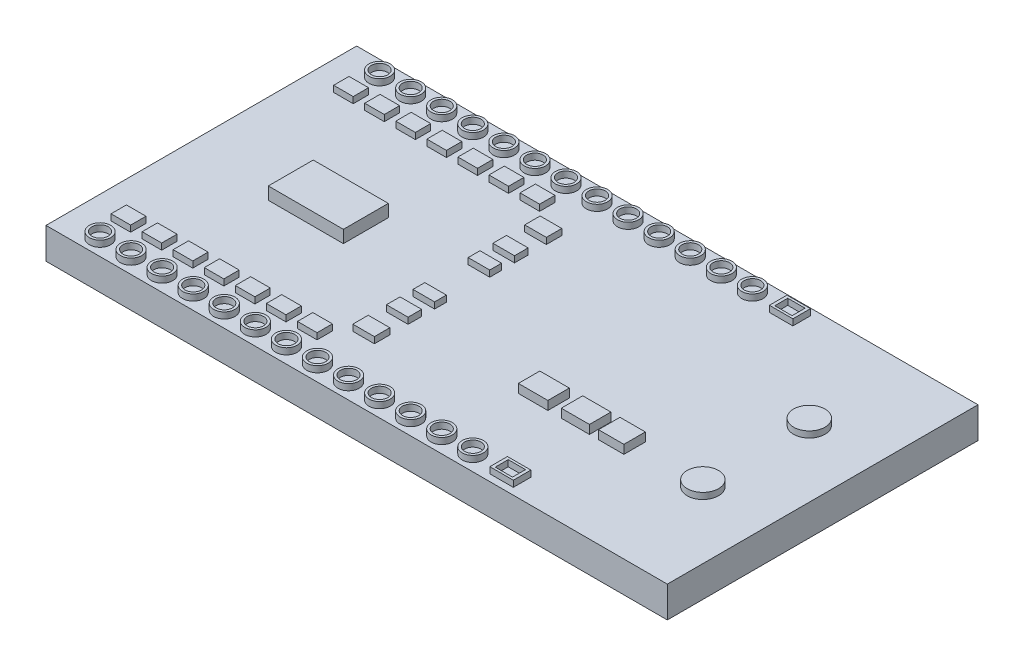
SolidWorks part; units mm, degrees
ref_plane "Front Plane" through (0, 0, 0) normal (0, 0, 1) x (1, 0, 0)
ref_plane "Top Plane" through (0, 0, 0) normal (0, 1, 0) x (1, 0, 0)
ref_plane "Right Plane" through (0, 0, 0) normal (1, 0, 0) x (0, 0, -1)
sketch "Sketch1" plane through (0, 0, 0) normal (0, 1, 0) x (1, 0, 0)
  line L1 (-25, 12.5) -> (25, 12.5)
  line L2 (-25, 12.5) -> (-25, -12.5)
  line L3 (-25, -12.5) -> (25, -12.5)
  line L4 (25, 12.5) -> (25, -12.5)
  line L5 (-25, 12.5) -> (25, -12.5) construction
  line L6 (-25, -12.5) -> (25, 12.5) construction
  point P0 (0, 0)
  dimension "D1" = 25
  dimension "D2" = 50
extrude "Boss-Extrude1" add sketch "Sketch1" along normal blind 2.5
sketch "Sketch2" plane through (0, 2.5, 0) normal (0, 1, 0) x (1, 0, 0)
  line L0 (-35.8947, 0) -> (29.0268, 0) construction
  line L1 (11.8135, -11.7711) -> (11.8135, -10.7261)
  line L2 (10.174, 11.956) -> (12.06, 11.956)
  line L3 (10.174, 11.956) -> (10.174, 10.5412)
  line L4 (10.174, 10.5412) -> (12.06, 10.5412)
  line L5 (12.06, 11.956) -> (12.06, 10.5412)
  line L6 (12.06, -11.956) -> (12.06, -10.5412)
  line L7 (10.174, -11.956) -> (12.06, -11.956)
  line L8 (10.4205, 11.7711) -> (11.8135, 11.7711)
  line L9 (10.4205, 11.7711) -> (10.4205, 10.7261)
  line L10 (10.4205, 10.7261) -> (11.8135, 10.7261)
  line L11 (11.8135, 11.7711) -> (11.8135, 10.7261)
  line L12 (10.4205, -11.7711) -> (11.8135, -11.7711)
  line L13 (10.174, -10.5412) -> (12.06, -10.5412)
  line L14 (10.4205, -10.7261) -> (11.8135, -10.7261)
  line L15 (10.4205, -11.7711) -> (10.4205, -10.7261)
  line L16 (10.174, -11.956) -> (10.174, -10.5412)
  line L17 (-20.1913, 9.5736) -> (-20.1913, 8.3389)
  line L18 (-22.6913, 9.5736) -> (-21.1163, 9.5736)
  line L19 (-22.6913, 9.5736) -> (-22.6913, 8.3389)
  line L20 (-22.6913, 8.3389) -> (-21.1163, 8.3389)
  line L21 (-21.1163, 9.5736) -> (-21.1163, 8.3389)
  line L22 (-22.6913, 9.5736) -> (-21.1163, 8.3389) construction
  line L23 (-22.6913, 8.3389) -> (-21.1163, 9.5736) construction
  line L24 (-20.1913, 9.5736) -> (-18.6163, 9.5736)
  line L25 (-18.6163, 9.5736) -> (-18.6163, 8.3389)
  line L26 (-20.1913, 8.3389) -> (-18.6163, 8.3389)
  line L27 (-17.6913, 9.5736) -> (-17.6913, 8.3389)
  line L28 (-17.6913, 9.5736) -> (-16.1163, 9.5736)
  line L29 (-16.1163, 9.5736) -> (-16.1163, 8.3389)
  line L30 (-17.6913, 8.3389) -> (-16.1163, 8.3389)
  line L31 (-15.1913, 9.5736) -> (-15.1913, 8.3389)
  line L32 (-15.1913, 9.5736) -> (-13.6163, 9.5736)
  line L33 (-13.6163, 9.5736) -> (-13.6163, 8.3389)
  line L34 (-15.1913, 8.3389) -> (-13.6163, 8.3389)
  line L35 (-12.6913, 9.5736) -> (-12.6913, 8.3389)
  line L36 (-12.6913, 9.5736) -> (-11.1163, 9.5736)
  line L37 (-11.1163, 9.5736) -> (-11.1163, 8.3389)
  line L38 (-12.6913, 8.3389) -> (-11.1163, 8.3389)
  line L39 (-10.1913, 9.5736) -> (-10.1913, 8.3389)
  line L40 (-10.1913, 9.5736) -> (-8.6163, 9.5736)
  line L41 (-8.6163, 9.5736) -> (-8.6163, 8.3389)
  line L42 (-10.1913, 8.3389) -> (-8.6163, 8.3389)
  line L43 (-7.6913, 9.5736) -> (-7.6913, 8.3389)
  line L44 (-7.6913, 9.5736) -> (-6.1163, 9.5736)
  line L45 (-6.1163, 9.5736) -> (-6.1163, 8.3389)
  line L46 (-7.6913, 8.3389) -> (-6.1163, 8.3389)
  line L47 (-7.6913, -9.5736) -> (-6.1163, -9.5736)
  line L48 (-6.1163, -9.5736) -> (-6.1163, -8.3389)
  line L49 (-7.6913, -8.3389) -> (-6.1163, -8.3389)
  line L50 (-7.6913, -9.5736) -> (-7.6913, -8.3389)
  line L51 (-10.1913, -9.5736) -> (-8.6163, -9.5736)
  line L52 (-8.6163, -9.5736) -> (-8.6163, -8.3389)
  line L53 (-10.1913, -8.3389) -> (-8.6163, -8.3389)
  line L54 (-10.1913, -9.5736) -> (-10.1913, -8.3389)
  line L55 (-12.6913, -9.5736) -> (-11.1163, -9.5736)
  line L56 (-11.1163, -9.5736) -> (-11.1163, -8.3389)
  line L57 (-12.6913, -8.3389) -> (-11.1163, -8.3389)
  line L58 (-12.6913, -9.5736) -> (-12.6913, -8.3389)
  line L59 (-15.1913, -9.5736) -> (-13.6163, -9.5736)
  line L60 (-13.6163, -9.5736) -> (-13.6163, -8.3389)
  line L61 (-15.1913, -8.3389) -> (-13.6163, -8.3389)
  line L62 (-15.1913, -9.5736) -> (-15.1913, -8.3389)
  line L63 (-17.6913, -9.5736) -> (-16.1163, -9.5736)
  line L64 (-16.1163, -9.5736) -> (-16.1163, -8.3389)
  line L65 (-17.6913, -8.3389) -> (-16.1163, -8.3389)
  line L66 (-17.6913, -9.5736) -> (-17.6913, -8.3389)
  line L67 (-20.1913, -9.5736) -> (-18.6163, -9.5736)
  line L68 (-18.6163, -9.5736) -> (-18.6163, -8.3389)
  line L69 (-20.1913, -8.3389) -> (-18.6163, -8.3389)
  line L70 (-20.1913, -9.5736) -> (-20.1913, -8.3389)
  line L71 (-22.6913, -8.3389) -> (-21.1163, -8.3389)
  line L72 (-21.1163, -9.5736) -> (-21.1163, -8.3389)
  line L73 (-22.6913, -9.5736) -> (-21.1163, -9.5736)
  line L74 (-22.6913, -9.5736) -> (-22.6913, -8.3389)
  line L75 (-5.2732, -6.2958) -> (-3.5344, -6.2958)
  line L76 (-5.2732, 7.5383) -> (-3.5344, 7.5383)
  line L77 (-5.2732, 7.5383) -> (-5.2732, 6.2958)
  line L78 (-5.2732, 6.2958) -> (-3.5344, 6.2958)
  line L79 (-3.5344, 7.5383) -> (-3.5344, 6.2958)
  line L80 (-5.2732, 7.5383) -> (-3.5344, 6.2958) construction
  line L81 (-5.2732, 6.2958) -> (-3.5344, 7.5383) construction
  line L82 (-5.2732, 4.8291) -> (-3.5344, 4.8291)
  line L83 (-5.2732, 4.8291) -> (-5.2732, 3.7363)
  line L84 (-5.2732, 3.7363) -> (-3.5344, 3.7363)
  line L85 (-3.5344, 4.8291) -> (-3.5344, 3.7363)
  line L86 (-5.2732, 4.8291) -> (-3.5344, 3.7363) construction
  line L87 (-5.2732, 3.7363) -> (-3.5344, 4.8291) construction
  line L88 (-5.2732, 2.6954) -> (-3.5344, 2.6954)
  line L89 (-5.2732, 2.6954) -> (-5.2732, 1.7437)
  line L90 (-5.2732, 1.7437) -> (-3.5344, 1.7437)
  line L91 (-3.5344, 2.6954) -> (-3.5344, 1.7437)
  line L92 (-5.2732, 2.6954) -> (-3.5344, 1.7437) construction
  line L93 (-5.2732, 1.7437) -> (-3.5344, 2.6954) construction
  line L94 (-3.5344, -7.5383) -> (-3.5344, -6.2958)
  line L95 (-5.2732, -7.5383) -> (-3.5344, -7.5383)
  line L96 (-5.2732, -7.5383) -> (-5.2732, -6.2958)
  line L97 (-5.2732, -3.7363) -> (-3.5344, -3.7363)
  line L98 (-3.5344, -4.8291) -> (-3.5344, -3.7363)
  line L99 (-5.2732, -4.8291) -> (-3.5344, -4.8291)
  line L100 (-5.2732, -4.8291) -> (-5.2732, -3.7363)
  line L101 (-5.2732, -1.7437) -> (-3.5344, -1.7437)
  line L102 (-3.5344, -2.6954) -> (-3.5344, -1.7437)
  line L103 (-5.2732, -2.6954) -> (-3.5344, -2.6954)
  line L104 (-5.2732, -2.6954) -> (-5.2732, -1.7437)
  line L105 (-5.2732, -1.7437) -> (-3.5344, -2.6954) construction
  line L106 (-5.2732, -2.6954) -> (-3.5344, -1.7437) construction
  circle A0 centre (-21.9038, 11.2486) radius 0.6585
  circle A1 centre (-21.9038, 11.2486) radius 0.858
  circle A2 centre (-19.4038, 11.2486) radius 0.6585
  circle A3 centre (-19.4038, 11.2486) radius 0.858
  circle A4 centre (-16.9038, 11.2486) radius 0.6585
  circle A5 centre (-16.9038, 11.2486) radius 0.858
  circle A6 centre (-14.4038, 11.2486) radius 0.6585
  circle A7 centre (-14.4038, 11.2486) radius 0.858
  circle A8 centre (-11.9038, 11.2486) radius 0.6585
  circle A9 centre (-11.9038, 11.2486) radius 0.858
  circle A10 centre (-9.4038, 11.2486) radius 0.6585
  circle A11 centre (-9.4038, 11.2486) radius 0.858
  circle A12 centre (-6.9038, 11.2486) radius 0.6585
  circle A13 centre (-6.9038, 11.2486) radius 0.858
  circle A14 centre (-4.4038, 11.2486) radius 0.6585
  circle A15 centre (-4.4038, 11.2486) radius 0.858
  circle A16 centre (-1.9038, 11.2486) radius 0.6585
  circle A17 centre (-1.9038, 11.2486) radius 0.858
  circle A18 centre (0.5962, 11.2486) radius 0.6585
  circle A19 centre (0.5962, 11.2486) radius 0.858
  circle A20 centre (3.0962, 11.2486) radius 0.6585
  circle A21 centre (3.0962, 11.2486) radius 0.858
  circle A22 centre (5.5962, 11.2486) radius 0.6585
  circle A23 centre (5.5962, 11.2486) radius 0.858
  circle A24 centre (8.0962, 11.2486) radius 0.6585
  circle A25 centre (8.0962, 11.2486) radius 0.858
  circle A26 centre (-9.4038, -11.2486) radius 0.858
  circle A27 centre (-11.9038, -11.2486) radius 0.858
  circle A28 centre (-11.9038, -11.2486) radius 0.6585
  circle A29 centre (-14.4038, -11.2486) radius 0.858
  circle A30 centre (-4.4038, -11.2486) radius 0.6585
  circle A31 centre (-6.9038, -11.2486) radius 0.6585
  circle A32 centre (-9.4038, -11.2486) radius 0.6585
  circle A33 centre (-14.4038, -11.2486) radius 0.6585
  circle A34 centre (-16.9038, -11.2486) radius 0.858
  circle A35 centre (-16.9038, -11.2486) radius 0.6585
  circle A36 centre (-19.4038, -11.2486) radius 0.858
  circle A37 centre (-19.4038, -11.2486) radius 0.6585
  circle A38 centre (-21.9038, -11.2486) radius 0.6585
  circle A39 centre (-21.9038, -11.2486) radius 0.858
  circle A40 centre (5.5962, -11.2486) radius 0.6585
  circle A41 centre (5.5962, -11.2486) radius 0.858
  circle A42 centre (8.0962, -11.2486) radius 0.858
  circle A43 centre (8.0962, -11.2486) radius 0.6585
  circle A44 centre (3.0962, -11.2486) radius 0.6585
  circle A45 centre (3.0962, -11.2486) radius 0.858
  circle A46 centre (0.5962, -11.2486) radius 0.858
  circle A47 centre (0.5962, -11.2486) radius 0.6585
  circle A48 centre (-1.9038, -11.2486) radius 0.6585
  circle A49 centre (-1.9038, -11.2486) radius 0.858
  circle A50 centre (-4.4038, -11.2486) radius 0.858
  circle A51 centre (-6.9038, -11.2486) radius 0.858
  circle A52 centre (19.6422, 4.2827) radius 1.2648
  circle A53 centre (19.6422, -4.2827) radius 1.2648
  point P7 (11.117, 11.2486)
  point P47 (11.117, 11.2486)
  point P99 (-21.9038, 8.9563)
  point P156 (-4.4038, 6.917)
  point P161 (-4.4038, 4.2827)
  point P166 (-4.4038, 2.2195)
  point P183 (-4.4038, -2.2195)
  dimension "D1" = 13
  dimension "D2" = 7
extrude "Boss-Extrude2" add sketch "Sketch2" along normal blind 0.5
sketch "Sketch3" plane through (0, 2.5, 0) normal (0, 1, 0) x (1, 0, 0)
  line L1 (-17.8036, 1.8073) -> (-11.7611, 1.8073)
  line L2 (-17.8036, 1.8073) -> (-17.8036, -1.8073)
  line L3 (-17.8036, -1.8073) -> (-11.7611, -1.8073)
  line L4 (-11.7611, 1.8073) -> (-11.7611, -1.8073)
  line L5 (-17.8036, 1.8073) -> (-11.7611, -1.8073) construction
  line L6 (-17.8036, -1.8073) -> (-11.7611, 1.8073) construction
  point P0 (-14.7824, 0)
extrude "Boss-Extrude3" add sketch "Sketch3" along normal blind 1
sketch "Sketch4" plane through (0, 2.5, 0) normal (0, 1, 0) x (1, 0, 0)
  line L1 (5.7187, -3.4798) -> (8.0925, -3.4798)
  line L2 (5.7187, -3.4798) -> (5.7187, -5.2062)
  line L3 (5.7187, -5.2062) -> (8.0925, -5.2062)
  line L4 (8.0925, -3.4798) -> (8.0925, -5.2062)
  line L5 (5.7187, -3.4798) -> (8.0925, -5.2062) construction
  line L6 (5.7187, -5.2062) -> (8.0925, -3.4798) construction
  line L7 (9.1715, -3.4798) -> (11.4374, -3.4798)
  line L8 (9.1715, -3.4798) -> (9.1715, -5.2062)
  line L9 (9.1715, -5.2062) -> (11.4374, -5.2062)
  line L10 (11.4374, -3.4798) -> (11.4374, -5.2062)
  line L11 (9.1715, -3.4798) -> (11.4374, -5.2062) construction
  line L12 (9.1715, -5.2062) -> (11.4374, -3.4798) construction
  line L13 (12.1693, -3.4798) -> (14.2094, -3.4798)
  line L14 (12.1693, -3.4798) -> (12.1693, -5.2062)
  line L15 (12.1693, -5.2062) -> (14.2094, -5.2062)
  line L16 (14.2094, -3.4798) -> (14.2094, -5.2062)
  line L17 (12.1693, -3.4798) -> (14.2094, -5.2062) construction
  line L18 (12.1693, -5.2062) -> (14.2094, -3.4798) construction
  point P0 (6.9056, -4.343)
  point P5 (10.3045, -4.343)
  point P10 (13.1893, -4.343)
extrude "Boss-Extrude4" add sketch "Sketch4" along normal blind 0.7
